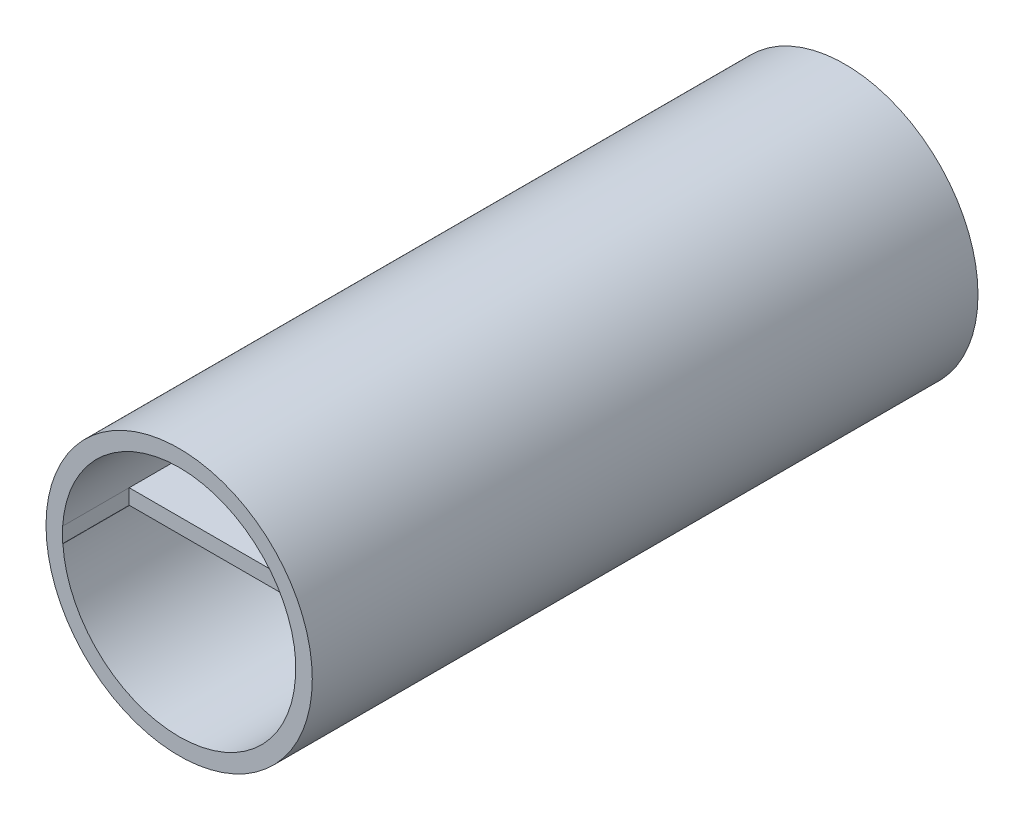
SolidWorks part; units mm, degrees
ref_plane "Front Plane" through (0, 0, 0) normal (0, 0, 1) x (1, 0, 0)
ref_plane "Top Plane" through (0, 0, 0) normal (0, 1, 0) x (1, 0, 0)
ref_plane "Right Plane" through (0, 0, 0) normal (1, 0, 0) x (0, 0, -1)
sketch "Sketch2" plane through (0, 0, 0) normal (0, 0, 1) x (1, 0, 0)
  line L5 (-34.9261, -2.2734) -> (34.9261, -2.2734)
  line L7 (-35, 2.2782) -> (35, 2.2782)
  line L9 (-34.9261, -2.2734) -> (35, 2.2782) construction
  line L10 (-35, 2.2782) -> (34.9261, -2.2734) construction
  arc A0 (-34.9261, -2.2734) -> (34.9261, -2.2734) centre (0, 0) ccw
  circle A1 centre (0, 0) radius 40
  circle A2 centre (0, 0) radius 35 construction
  arc A3 (35, 2.2782) -> (-35, 2.2782) centre (0, 0) ccw
  dimension "D1" = 70
  dimension "D3" = 70
  dimension "D2" = 5
extrude "Boss-Extrude1" add sketch "Sketch2" along normal mid plane 200 contours A0
sketch "Sketch4" plane through (0, 0, 100) normal (0, 0, 1) x (1, 0, 0)
  line L1 (-35, -2.2782) -> (35, -2.2782)
  line L2 (-35, -2.2782) -> (-35, 2.2782)
  line L3 (-35, 2.2782) -> (35, 2.2782)
  line L4 (35, -2.2782) -> (35, 2.2782)
  line L5 (-35, -2.2782) -> (35, 2.2782) construction
  line L6 (-35, 2.2782) -> (35, -2.2782) construction
  point P0 (0, 0)
extrude "Cut-Extrude1" cut sketch "Sketch4" against normal blind 20
sketch "Sketch5" plane through (0, 0, -100) normal (0, 0, -1) x (-1, 0, 0)
  line L1 (-35, -2.2782) -> (35, -2.2782)
  line L2 (-35, -2.2782) -> (-35, 2.2782)
  line L3 (-35, 2.2782) -> (35, 2.2782)
  line L4 (35, -2.2782) -> (35, 2.2782)
  line L5 (-35, -2.2782) -> (35, 2.2782) construction
  line L6 (-35, 2.2782) -> (35, -2.2782) construction
  point P0 (0, 0)
extrude "Cut-Extrude2" cut sketch "Sketch5" against normal blind 20
